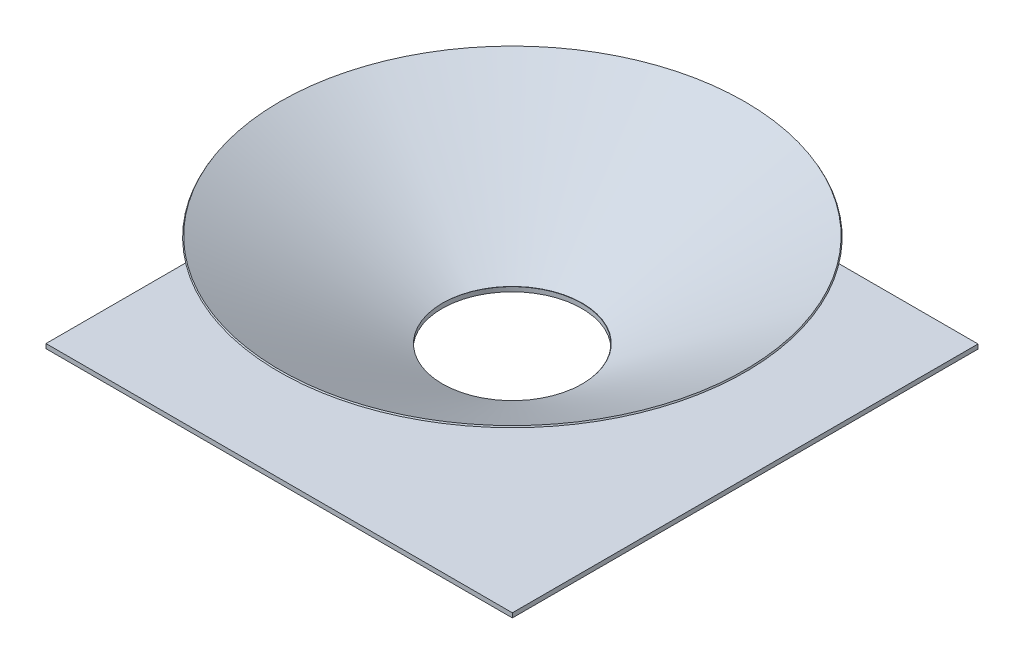
SolidWorks part; units mm, degrees
ref_plane "Front Plane" through (0, 0, 0) normal (0, 0, 1) x (1, 0, 0)
ref_plane "Top Plane" through (0, 0, 0) normal (0, 1, 0) x (1, 0, 0)
ref_plane "Right Plane" through (0, 0, 0) normal (1, 0, 0) x (0, 0, -1)
sketch "Sketch1" plane through (0, 0, 0) normal (0, 0, 1) x (1, 0, 0)
  line L0 (-48.8837, 0) -> (-156.25, 61.6327)
  line L1 (-156.25, 61.6327) -> (-155.7522, 62.5)
  line L2 (-155.7522, 62.5) -> (-46.875, 0)
  line L3 (-48.8837, 0) -> (-46.875, 0)
  line L4 (0, 0) -> (0, 38.049) construction
  line L5 (0, 0) -> (-37.9362, 0) construction
  dimension "D1" = 46.875
  dimension "D2" = 156.25
  dimension "D3" = 1
  dimension "D4" = 62.5
revolve "Revolve1" add sketch "Sketch1" angle 360 about L4
sketch "Sketch2" plane through (0, 0, 0) normal (0, 1, 0) x (1, 0, 0)
  line L0 (-156.25, -156.25) -> (156.25, -156.25)
  line L1 (-156.25, -156.25) -> (-156.25, 155.7522)
  line L2 (156.25, -156.25) -> (156.25, 155.7522)
  line L3 (-156.25, 155.7522) -> (156.25, 155.7522)
  line L4 (-156.25, -156.25) -> (156.25, 155.7522) construction
  line L5 (156.25, -156.25) -> (-156.25, 155.7522) construction
  circle A0 centre (0, -0.2489) radius 46.875
  circle A1 centre (0, 0) radius 156.25 construction
  circle A2 centre (0, 0) radius 155.7522 construction
  point P1 (0, -0.2489)
  dimension "D1" = 93.75
extrude "Boss-Extrude1" add sketch "Sketch2" against normal blind 3 separate body
sketch "Sketch3" plane through (0, 0, 0) normal (0, 0, 1) x (1, 0, 0)
  line L0 (-156.25, 61.6327) -> (-48.8837, 0) construction
  line L1 (-156.25, 0) -> (156.25, 0) construction
  line L2 (-65.8443, 9.7361) -> (-48.8837, 0)
  line L3 (-48.8837, 0) -> (-68.4401, 0)
  line L4 (0, 0) -> (0, 13.3849) construction
  arc A0 (-65.8443, 9.7361) -> (-68.4401, 0) centre (-68.4401, 5.2141) cw
revolve "Revolve2" add sketch "Sketch3" angle 360 about L4
